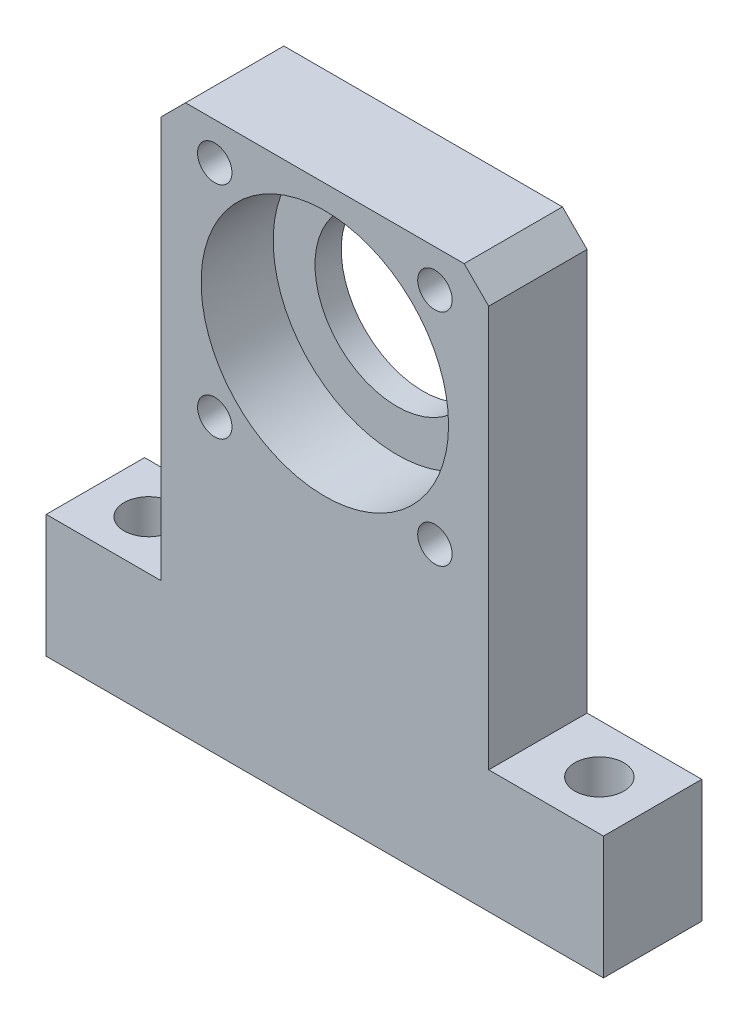
SolidWorks part; units mm, degrees
material "SKD11淬火HRC56-60"
ref_plane "前基準面" through (0, 0, 0) normal (0, 0, 1) x (1, 0, 0)
ref_plane "上基準面" through (0, 0, 0) normal (0, 1, 0) x (1, 0, 0)
ref_plane "右基準面" through (0, 0, 0) normal (1, 0, 0) x (0, 0, -1)
sketch "草图1" plane through (0, 0, 0) normal (0, 0, 1) x (1, 0, 0)
  line L1 (0, 0) -> (68, 0)
  line L2 (0, 0) -> (0, 67)
  line L3 (0, 67) -> (68, 67)
  line L4 (68, 0) -> (68, 67)
  dimension "D1" = 68
  dimension "D2" = 67
extrude "凸台-拉伸1" add sketch "草图1" along normal blind 12
sketch "草图2" plane through (0, 0, 12) normal (0, 0, 1) x (1, 0, 0)
  line L0 (34, 0) -> (34, 67) construction
  line L1 (0, 0) -> (68, 0) construction
  line L2 (68, 67) -> (0, 67) construction
  circle A0 centre (34, 49) radius 15.1
  dimension "D1" = 30.2
  dimension "D2" = 18
extrude "切除-拉伸1" cut sketch "草图2" against normal blind 8.8
sketch "草图3" plane through (0, 0, 3.2) normal (0, 0, 1) x (1, 0, 0)
  circle A0 centre (34, 49) radius 10
  dimension "D1" = 20
extrude "切除-拉伸2" cut sketch "草图3" against normal through all
hole_wizard "M5 螺纹孔1" positions "草图5" profile "草图6" tap size "M5" standard "ISO" end condition through all
sketch "草图5" plane through (0, 0, 12) normal (0, 0, 1) x (1, 0, 0)
  line L0 (34, 49) -> (61.9535, 49) construction
  line L1 (34, 49) -> (34, 67.6475) construction
  line L2 (34, 49) -> (52.0039, 67.0039) construction
  circle A0 centre (34, 49) radius 19
  point P0 (47.435, 62.435)
  point P1 (20.565, 62.435)
  point P3 (20.565, 35.565)
  point P5 (47.435, 35.565)
  dimension "D1" = 38
  dimension "D2" = 45
sketch "草图6" plane through (47.435, 62.435, 12) normal (1, 0, 0) x (0, -1, 0)
  line L0 (0, 0) -> (0, 12)
  line L1 (0, 12) -> (2.1, 12)
  line L2 (2.1, 12) -> (2.1, 0)
  line L5 (2.1, 0) -> (0, 0)
  line L11 (0, -6.35) -> (0, 107.95) construction
  dimension "通孔螺纹孔钻头直径" = 4.2
  dimension "通孔螺纹孔钻头深度" = 12
cosmetic thread "孔螺蚊线1" parameters "D2"=5
cosmetic thread "孔螺蚊线2" parameters "D2"=5
cosmetic thread "孔螺蚊线3" parameters "D2"=5
cosmetic thread "孔螺蚊线4" parameters "D2"=5
sketch "草图7" plane through (0, 0, 12) normal (0, 0, 1) x (1, 0, 0)
  line L0 (34, 0) -> (34, 16.4595) construction
  line L1 (0, 67) -> (14, 67)
  line L2 (0, 67) -> (0, 15)
  line L3 (0, 15) -> (14, 15)
  line L4 (14, 67) -> (14, 15)
  line L5 (0, 0) -> (68, 0) construction
  line L6 (54, 67) -> (54, 15)
  line L7 (68, 15) -> (54, 15)
  line L8 (68, 67) -> (68, 15)
  line L9 (68, 67) -> (54, 67)
  dimension "D1" = 15
  dimension "D2" = 14
extrude "切除-拉伸3" cut sketch "草图7" against normal through all
chamfer "倒角1" distance 3 angle 45 2 edges at (54, 67, 6) (14, 67, 6)
sketch "草图8" plane through (0, 0, 0) normal (0, -1, 0) x (1, 0, 0)
  line L0 (0, 6) -> (68, 6) construction
  line L1 (0, 12) -> (0, 0) construction
  line L2 (68, 12) -> (68, 0) construction
  line L3 (34, 12) -> (34, 0) construction
  line L4 (0, 12) -> (68, 12) construction
  line L5 (0, 0) -> (68, 0) construction
  circle A0 centre (6.5, 6) radius 3
  circle A1 centre (61.5, 6) radius 3
  dimension "D1" = 6
  dimension "D2" = 6.5
extrude "切除-拉伸4" cut sketch "草图8" against normal through all
